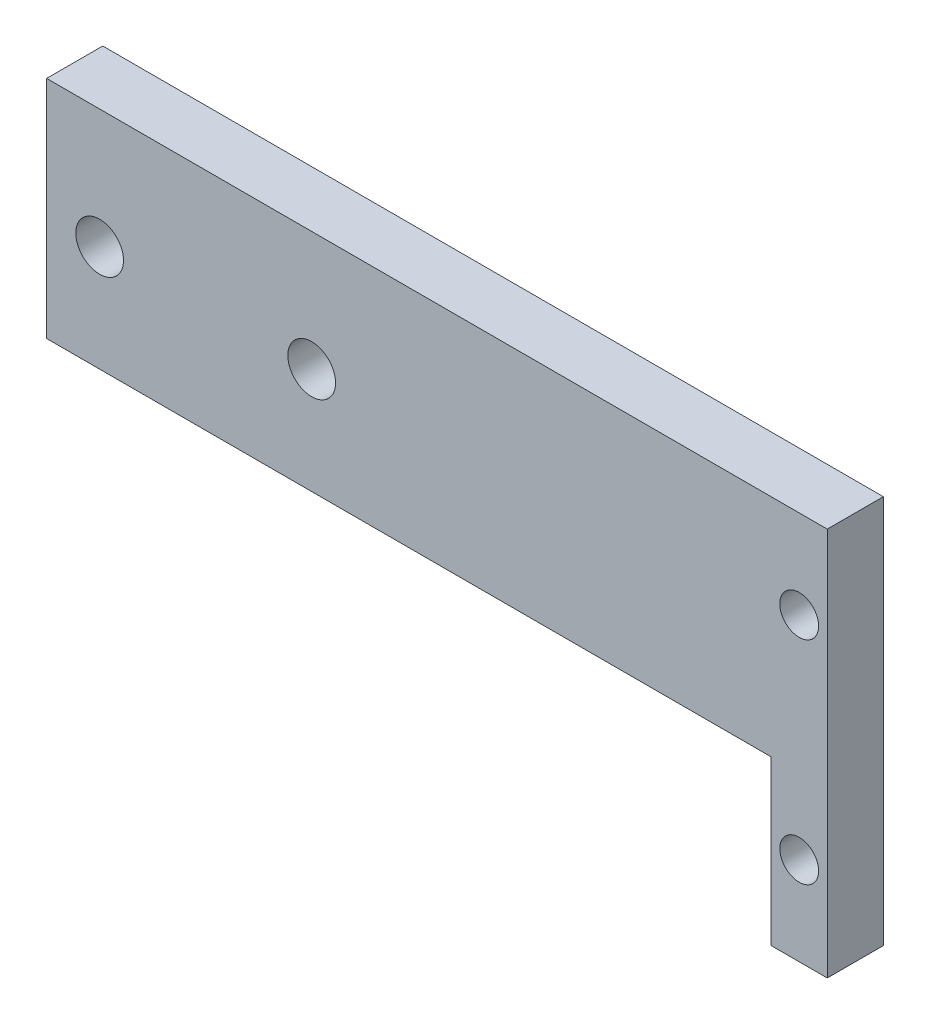
SolidWorks part; units mm, degrees
ref_plane "Front Plane" through (0, 0, 0) normal (0, 0, 1) x (1, 0, 0)
ref_plane "Top Plane" through (0, 0, 0) normal (0, 1, 0) x (1, 0, 0)
ref_plane "Right Plane" through (0, 0, 0) normal (1, 0, 0) x (0, 0, -1)
sketch "Sketch1" plane through (0, 0, 0) normal (0, 0, 1) x (1, 0, 0)
  line L0 (0, 0) -> (0, 9.25)
  line L1 (0, 9.25) -> (-41, 9.25)
  line L2 (-41, 9.25) -> (-41, 22)
  line L3 (-41, 22) -> (3.175, 22)
  line L4 (3.175, 22) -> (3.175, 0)
  line L5 (3.175, 0) -> (0, 0)
  line L6 (-38, 15.25) -> (-26, 15.25) construction
  dimension "D1" = 3.175
  dimension "D2" = 15.25
  dimension "D3" = 12
  dimension "D4" = 41
  dimension "D5" = 38
  dimension "D6" = 6
  dimension "D7" = 22
extrude "Boss-Extrude1" add sketch "Sketch1" along normal blind 3.175
hole_wizard "M2.5 Clearance Hole1" positions "Sketch2" profile "Sketch3" hole size "M2.5" standard "ANSI Metric" end condition through all
sketch "Sketch2" plane through (0, 0, 3.175) normal (0, 0, 1) x (1, 0, 0)
  line L0 (3.175, 11) -> (0, 11) construction
  line L1 (3.175, 22) -> (3.175, 0) construction
  line L3 (1.5875, 17) -> (1.5875, 11) construction
  point P0 (-38, 15.25)
  point P3 (-26, 15.25)
  dimension "D1" = 6
sketch "Sketch3" plane through (-38, 15.25, 3.175) normal (1, 0, 0) x (0, -1, 0)
  line L0 (0, 0) -> (0, 3.175)
  line L1 (0, 3.175) -> (1.35, 3.175)
  line L2 (1.35, 3.175) -> (1.35, 0)
  line L5 (1.35, 0) -> (0, 0)
  line L11 (0, -6.35) -> (0, 107.95) construction
  dimension "Thru Hole Dia." = 2.7
  dimension "Thru Hole Depth" = 3.175
hole_wizard "M2 Clearance Hole1" positions "Sketch4" profile "Sketch5" hole size "M2" standard "ANSI Metric" end condition through all
sketch "Sketch4" plane through (0, 0, 3.175) normal (0, 0, 1) x (1, 0, 0)
  line L0 (0, 11) -> (3.175, 11) construction
  point P0 (1.5875, 17)
  point P10 (1.5875, 5)
sketch "Sketch5" plane through (1.5875, 17, 3.175) normal (1, 0, 0) x (0, -1, 0)
  line L0 (0, 0) -> (0, 3.175)
  line L1 (0, 3.175) -> (1.1, 3.175)
  line L2 (1.1, 3.175) -> (1.1, 0)
  line L5 (1.1, 0) -> (0, 0)
  line L11 (0, -6.35) -> (0, 107.95) construction
  dimension "Thru Hole Dia." = 2.2
  dimension "Thru Hole Depth" = 3.175
